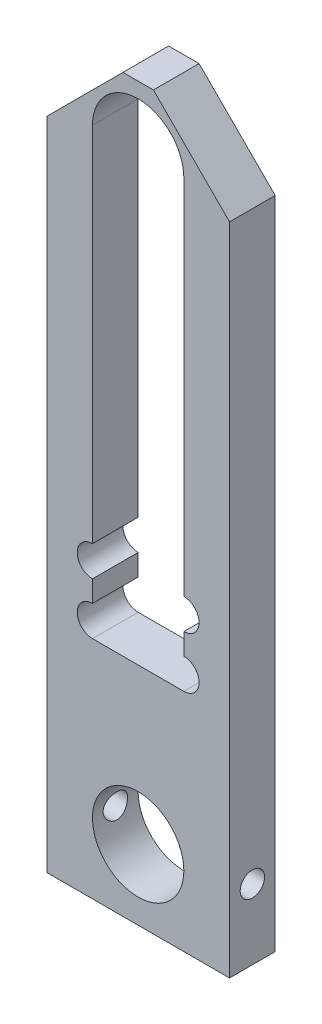
SolidWorks part; units mm, degrees
material "PW80:Mi:0:5:C1:0:1:2:Re:26:"
ref_plane "Plan1" through (0, 0, 0) normal (0, 0, 1) x (1, 0, 0)
ref_plane "Plan2" through (0, 0, 0) normal (0, 1, 0) x (1, 0, 0)
ref_plane "Plan3" through (0, 0, 0) normal (1, 0, 0) x (0, 0, -1)
sketch "Esquisse1" plane through (0, 0, 0) normal (0, 0, 1) x (1, 0, 0)
  line L0 (0, 215) -> (25, 240)
  line L1 (0, 0) -> (60, 0)
  line L2 (0, 0) -> (0, 215)
  line L3 (25, 240) -> (35, 240)
  line L4 (60, 0) -> (60, 215)
  line L5 (35, 240) -> (60, 215)
extrude "Base-Extrusion" add sketch "Esquisse1" along normal blind 15
sketch "Esquisse2" plane through (0, 0, 15) normal (0, 0, 1) x (1, 0, 0)
  circle A0 centre (30, 23) radius 15
extrude "Enlèv. mat.-Extru.1" cut sketch "Esquisse2" against normal blind 15
sketch "Esquisse3" plane through (0, 0, 15) normal (0, 0, 1) x (1, 0, 0)
  line L0 (45, 91) -> (45, 84)
  line L1 (15, 91) -> (15, 84)
  line L2 (15, 220) -> (15, 101)
  line L3 (15, 74) -> (45, 74)
  line L4 (45, 220) -> (45, 101)
  arc A0 (45, 220) -> (15, 220) centre (30, 220) ccw
  arc A1 (45, 74) -> (45, 84) centre (45, 79) ccw
  arc A2 (15, 84) -> (15, 74) centre (15, 79) ccw
  arc A3 (15, 101) -> (15, 91) centre (15, 96) ccw
  arc A4 (45, 91) -> (45, 101) centre (45, 96) ccw
extrude "Enlèv. mat.-Extru.2" cut sketch "Esquisse3" against normal blind 15
sketch "Esquisse4" plane through (0, 0, 0) normal (-1, 0, 0) x (0, 0, 1)
  circle A0 centre (7.5, 23) radius 4
extrude "Enlèv. mat.-Extru.3" cut sketch "Esquisse4" against normal through all
